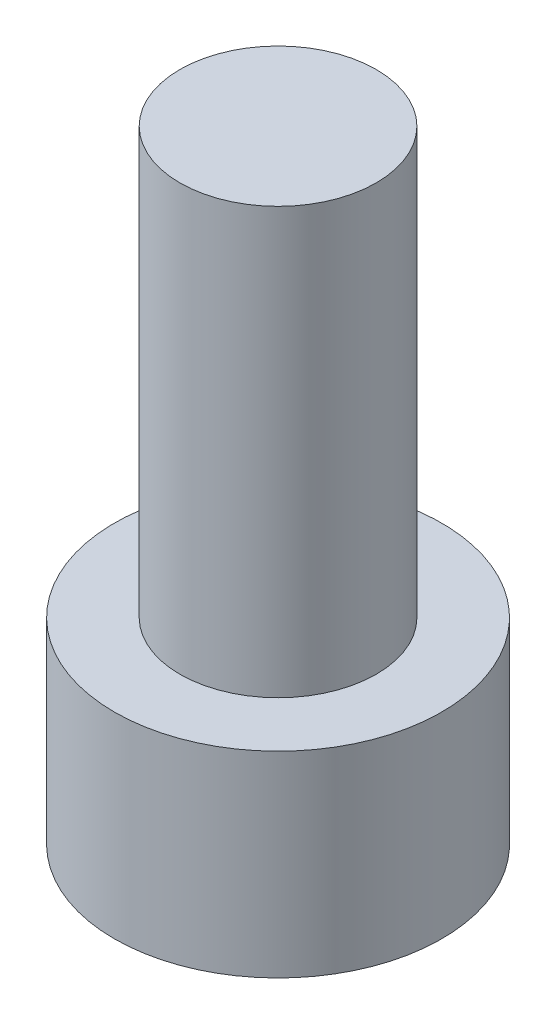
SolidWorks part; units mm, degrees
ref_plane "前视基准面" through (0, 0, 0) normal (0, 0, 1) x (1, 0, 0)
ref_plane "上视基准面" through (0, 0, 0) normal (0, 1, 0) x (1, 0, 0)
ref_plane "右视基准面" through (0, 0, 0) normal (1, 0, 0) x (0, 0, -1)
other "Configuration Table"
sketch "草图1" plane through (0, 0, 0) normal (0, 1, 0) x (1, 0, 0)
  circle A0 centre (0, 0) radius 5
  dimension "D1" = 10
extrude "凸台-拉伸1" add sketch "草图1" along normal blind 6
sketch "草图2" plane through (0, 6, 0) normal (0, 1, 0) x (1, 0, 0)
  circle A0 centre (0, 0) radius 3
  dimension "D1" = 6
extrude "凸台-拉伸2" add sketch "草图2" along normal blind 13
